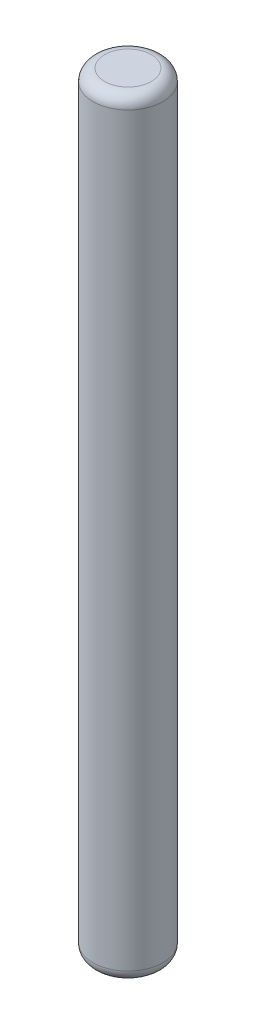
SolidWorks part; units mm, degrees
ref_plane "Face" through (0, 0, 0) normal (0, 0, 1) x (1, 0, 0)
ref_plane "Dessus" through (0, 0, 0) normal (0, 1, 0) x (1, 0, 0)
ref_plane "Droite" through (0, 0, 0) normal (1, 0, 0) x (0, 0, -1)
sketch "Esquisse1" plane through (0, 0, 0) normal (0, 1, 0) x (1, 0, 0)
  circle A0 centre (0, 0) radius 0.75
  dimension "D1" = 1.5
extrude "Boss.-Extru.1" add sketch "Esquisse1" along normal blind 16.5
fillet "Congé1" radius 0.25 2 edges at (0, 0, 0.75) (0, 16.5, 0.75)
